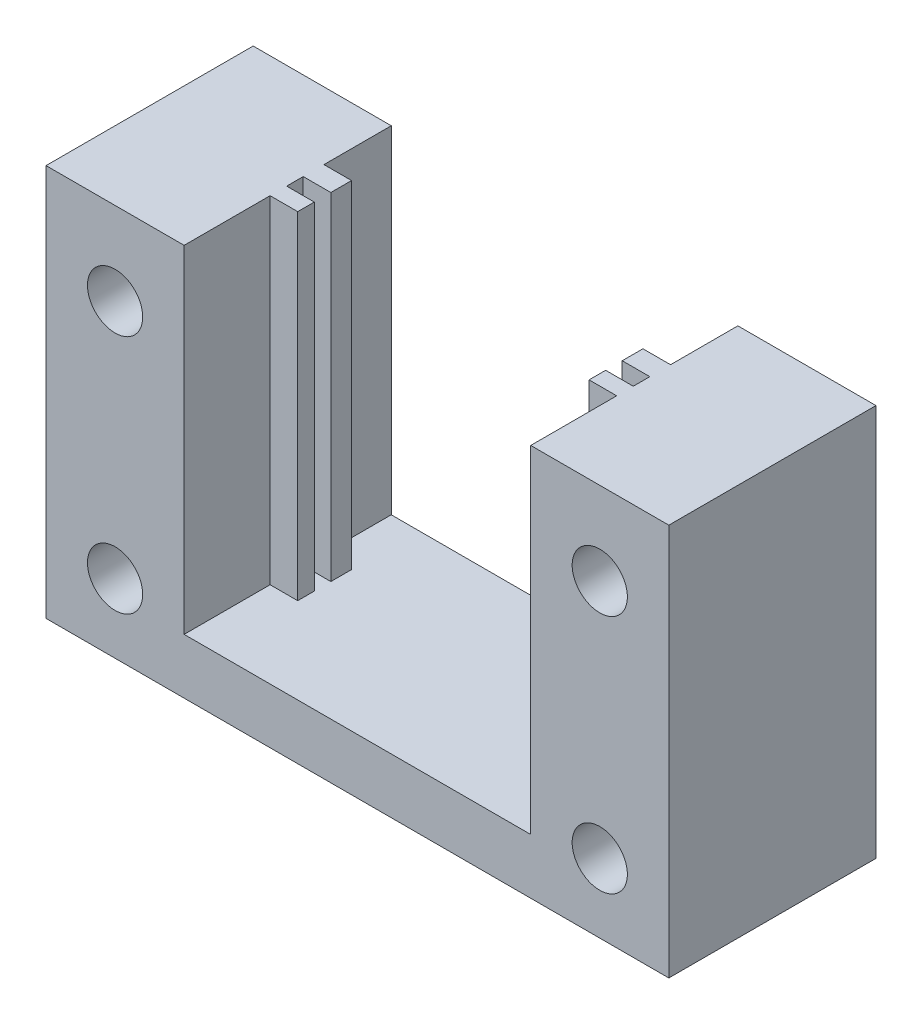
SolidWorks part; units mm, degrees
ref_plane "Plan de face" through (0, 0, 0) normal (0, 0, 1) x (1, 0, 0)
ref_plane "Plan de dessus" through (0, 0, 0) normal (0, 1, 0) x (1, 0, 0)
ref_plane "Plan de droite" through (0, 0, 0) normal (1, 0, 0) x (0, 0, -1)
sketch "Esquisse1" plane through (0, 0, 0) normal (0, 0, 1) x (1, 0, 0)
  line L0 (0, 0) -> (0, -27) construction
  line L1 (0, -27) -> (0, 30) construction
  line L2 (0, 0) -> (25.4165, -15.9375) construction
  line L3 (25.4165, -15.9375) -> (-22.8748, 14.3437) construction
  line L4 (-25.4165, -15.9375) -> (0, 0) construction
  line L5 (0, 0) -> (22.8748, 14.3437) construction
  line L6 (0, 30) -> (25.4165, -15.9375) construction
  line L8 (12.5, -14) -> (-12.5, -14)
  line L9 (12.5, -14) -> (12.5, -17)
  line L10 (12.5, -17) -> (-12.5, -17)
  line L11 (-12.5, -14) -> (-12.5, -17)
  circle A0 centre (0, 0) radius 37
  circle A1 centre (0, 30) radius 1.5
  circle A3 centre (-25.4165, -15.9375) radius 1.5
  circle A4 centre (0, -27) radius 1.5
  circle A5 centre (25.4165, -15.9375) radius 1.5
  dimension "D1" = 74
  dimension "D11" = 3
  dimension "D13" = 3
  dimension "D14" = 3
  dimension "D16" = 3
  dimension "D2" = 27
  dimension "D3" = 57
  dimension "D4" = 57
  dimension "D5" = 30
  dimension "D6" = 30
  dimension "D7" = 27
  dimension "D8" = 52.5
  dimension "D9" = 52.5
  dimension "D10" = 47.25
  dimension "D17" = 25
  dimension "D18" = 3
  dimension "D19" = 10
  dimension "D20" = 12.5
extrude "Boss.-Extru.1" add sketch "Esquisse1" along normal blind 2
sketch "Esquisse2" plane through (0, 0, 0) normal (0, 0, -1) x (-1, 0, 0)
  line L0 (-22.55, 14.9) -> (-22.55, -13.5)
  line L1 (-12.55, 14.9) -> (12.55, 14.9)
  line L2 (-12.55, 14.9) -> (-12.55, -9.5)
  line L3 (-12.55, -9.5) -> (12.55, -9.5)
  line L4 (12.55, 14.9) -> (12.55, -9.5)
  line L5 (-22.55, -13.5) -> (22.55, -13.5)
  line L6 (22.55, -13.5) -> (22.55, 14.9)
  line L7 (22.55, 14.9) -> (12.55, 14.9)
  line L8 (-22.55, 14.9) -> (-12.55, 14.9)
  point P0 (0, 0)
  dimension "D1" = 25.1
  dimension "D2" = 9.5
  dimension "D3" = 24.4
  dimension "D4" = 10
  dimension "D5" = 10
  dimension "D6" = 4
  dimension "D7" = 12.55
extrude "Boss.-Extru.2" add sketch "Esquisse2" along normal blind 15 contours L8 L0 L5 L6 L7 L4 L3 L2
sketch "Esquisse3" plane through (-12.55, 0, 0) normal (1, 0, 0) x (0, 0, -1)
  line L0 (15, 14.9) -> (0, 14.9) construction
  line L1 (10.125, 14.9) -> (8.625, 14.9)
  line L2 (10.125, 14.9) -> (10.125, -13.5)
  line L3 (10.125, -13.5) -> (8.625, -13.5)
  line L4 (8.625, 14.9) -> (8.625, -13.5)
  line L5 (15, -13.5) -> (0, -13.5) construction
  line L6 (0, 14.9) -> (7.5, 14.9) construction
  line L8 (6.225, 14.9) -> (7.425, 14.9)
  line L9 (6.225, 14.9) -> (6.225, -13.5)
  line L10 (6.225, -13.5) -> (7.425, -13.5)
  line L11 (7.425, 14.9) -> (7.425, -13.5)
  line L12 (8, 14.9) -> (8, -13.5) construction
  dimension "D1" = 1.5
  dimension "D2" = 0.625
  dimension "D3" = 1.2
  dimension "D4" = 1.2
  dimension "D5" = 0.575
  dimension "D6" = 0.5
extrude "Boss.-Extru.3" add sketch "Esquisse3" along normal blind 2 contours L11 L10 L9 L8 | L2 L3 L4 L1
sketch "Esquisse5" plane through (12.55, 0, 0) normal (-1, 0, 0) x (0, 0, 1)
  line L1 (-10.125, 14.9) -> (-8.625, 14.9)
  line L2 (-10.125, 14.9) -> (-10.125, -9.5)
  line L3 (-10.125, -9.5) -> (-8.625, -9.5)
  line L4 (-8.625, 14.9) -> (-8.625, -9.5)
  line L5 (-7.425, 14.9) -> (-6.225, 14.9)
  line L6 (-7.425, 14.9) -> (-7.425, -9.5)
  line L7 (-7.425, -9.5) -> (-6.225, -9.5)
  line L8 (-6.225, 14.9) -> (-6.225, -9.5)
extrude "Boss.-Extru.4" add sketch "Esquisse5" along normal blind 2
sketch "Esquisse10" plane through (0, 0, 2) normal (0, 0, 1) x (1, 0, 0)
  line L0 (22.55, -13.5) -> (-22.55, -13.5) construction
  line L1 (-22.55, -13.5) -> (-22.55, 14.9) construction
  line L2 (22.55, 14.9) -> (22.55, -13.5) construction
  line L3 (22.55, 14.9) -> (12.55, 14.9) construction
  line L4 (12.55, 14.9) -> (22.55, 14.9) construction
  circle A0 centre (-17.55, 8.9) radius 2
  circle A1 centre (-17.55, -8.5) radius 2
  circle A2 centre (17.55, -8.5) radius 2
  circle A3 centre (17.55, 8.9) radius 2
  dimension "D1" = 4
  dimension "D2" = 4
  dimension "D3" = 4
  dimension "D4" = 4
  dimension "D5" = 5
  dimension "D6" = 5
  dimension "D7" = 5
  dimension "D8" = 5
  dimension "D9" = 5
  dimension "D10" = 6
  dimension "D11" = 6
  dimension "D12" = 5
extrude "Enlèv. mat.-Extru.3" cut sketch "Esquisse10" against normal blind 49
sketch "Esquisse11" plane through (0, 0, 2) normal (0, 0, 1) x (1, 0, 0)
  circle A0 centre (0, 0) radius 37
extrude "Enlèv. mat.-Extru.4" cut sketch "Esquisse11" against normal blind 2
sketch "Sketch4" plane through (0, 0, -15) normal (0, 0, -1) x (-1, 0, 0)
  circle A0 centre (-17.55, -8.5) radius 3.5
  circle A1 centre (-17.55, 8.9) radius 3.5
  circle A2 centre (17.55, 8.9) radius 3.5
  circle A3 centre (17.55, -8.5) radius 3.5
  point P12 (0, 0)
  dimension "D1" = 7
  dimension "D2" = 7
  dimension "D3" = 7
  dimension "D4" = 7
extrude "Cut-Extrude2" cut sketch "Sketch4" against normal blind 3
